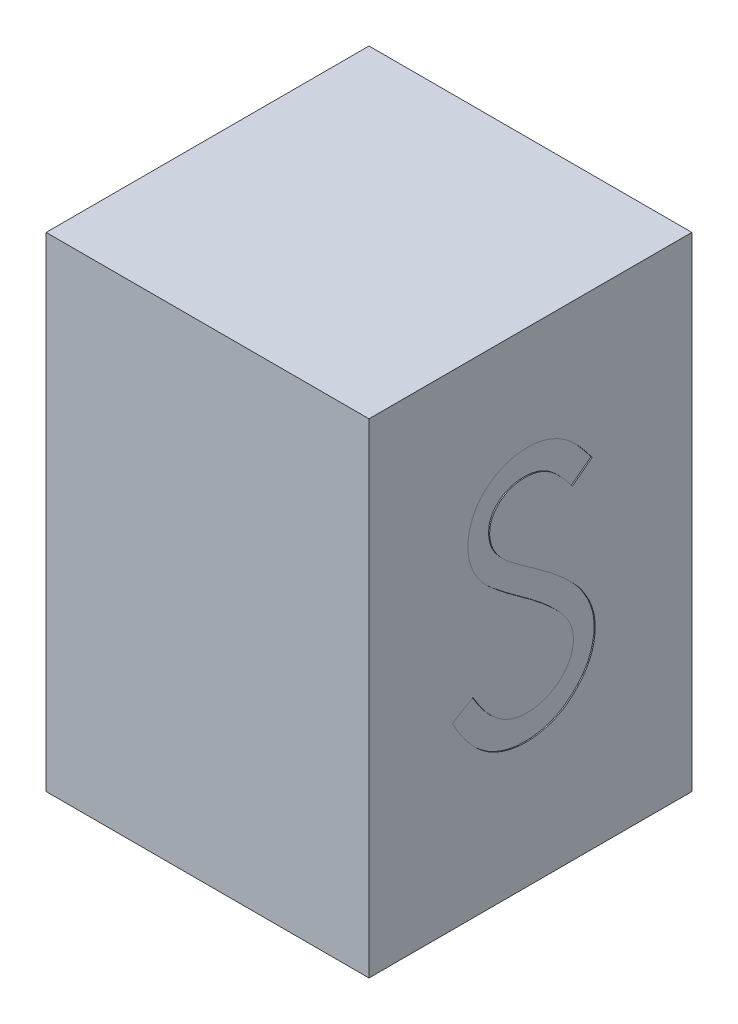
SolidWorks part; units mm, degrees
ref_plane "Front Plane" through (0, 0, 0) normal (0, 0, 1) x (1, 0, 0)
ref_plane "Top Plane" through (0, 0, 0) normal (0, 1, 0) x (1, 0, 0)
ref_plane "Right Plane" through (0, 0, 0) normal (1, 0, 0) x (0, 0, -1)
sketch "Sketch1" plane through (0, 0, 0) normal (0, 1, 0) x (1, 0, 0)
  line L1 (0, 0) -> (76.2, 0)
  line L2 (0, 0) -> (0, -76.2)
  line L3 (0, -76.2) -> (76.2, -76.2)
  line L4 (76.2, 0) -> (76.2, -76.2)
  dimension "D1" = 76.2
  dimension "D2" = 76.2
extrude "Boss-Extrude1" add sketch "Sketch1" along normal blind 114.3
sketch "Sketch2" plane through (76.2, 0, 0) normal (1, 0, 0) x (0, 0, -1)
  text T0 "S" font "Century Gothic" height 57.15
extrude "Cut-Extrude1" cut sketch "Sketch2" against normal blind 0.254
